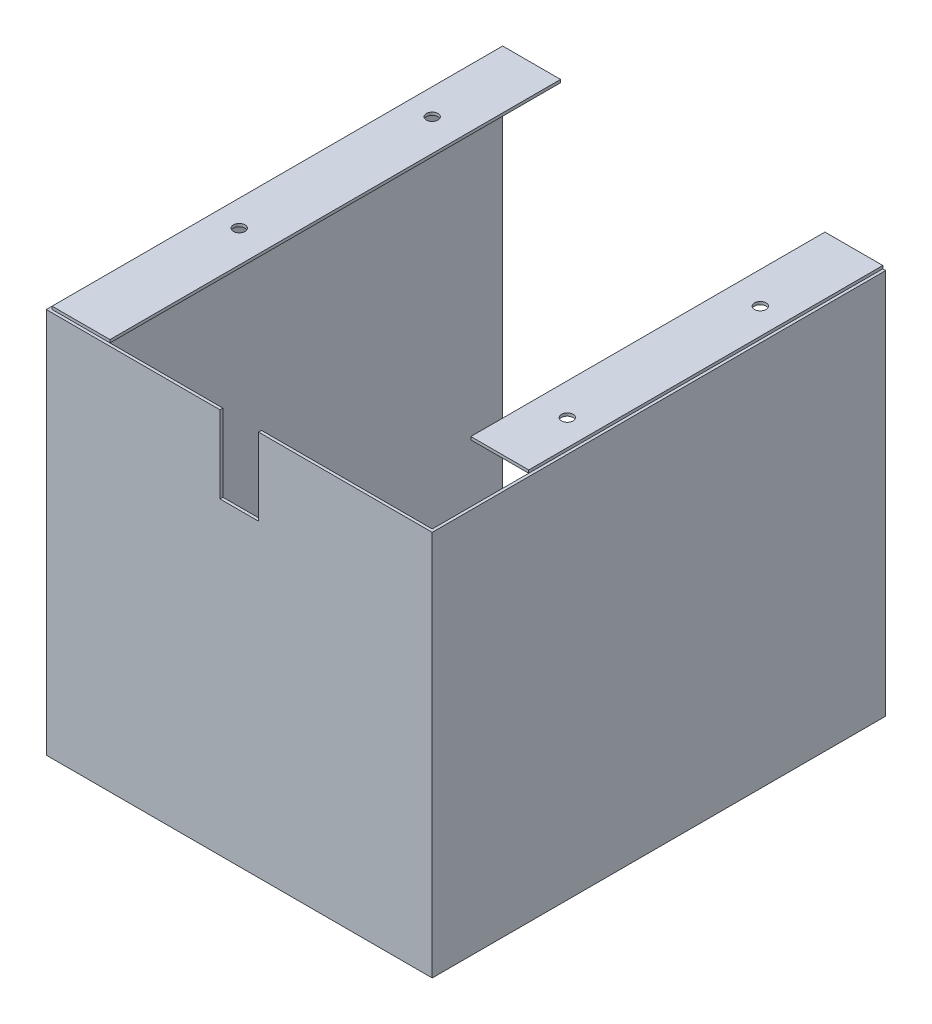
SolidWorks part; units mm, degrees
ref_plane "Front Plane" through (0, 0, 0) normal (0, 0, 1) x (1, 0, 0)
ref_plane "Top Plane" through (0, 0, 0) normal (0, 1, 0) x (1, 0, 0)
ref_plane "Right Plane" through (0, 0, 0) normal (1, 0, 0) x (0, 0, -1)
sketch "Sketch1" plane through (0, 0, 0) normal (0, 0, 1) x (1, 0, 0)
  line L1 (100, -100) -> (-100, -100)
  line L2 (100, -100) -> (100, 100)
  line L3 (100, 100) -> (-100, 100)
  line L4 (-100, -100) -> (-100, 100)
  line L5 (100, -100) -> (-100, 100) construction
  line L6 (100, 100) -> (-100, -100) construction
  point P0 (0, 0)
  dimension "D1" = 200
  dimension "D2" = 200
extrude "Boss-Extrude1" add sketch "Sketch1" along normal blind 235
shell "Shell1" thickness 1.5
sketch "Sketch2" plane through (0, 0, 235) normal (0, 0, 1) x (1, 0, 0)
  line L0 (0, 0) -> (0, 100) construction
  line L1 (100, 100) -> (-100, 100) construction
  line L3 (-10, 100) -> (10, 100)
  line L4 (-10, 100) -> (-10, 60)
  line L5 (-10, 60) -> (10, 60)
  line L6 (10, 100) -> (10, 60)
  dimension "D1" = 20
  dimension "D2" = 10
  dimension "D3" = 40
extrude "Cut-Extrude1" cut sketch "Sketch2" against normal up to next
sketch "Sketch3" plane through (0, 100, 0) normal (0, 1, 0) x (1, 0, 0)
  line L0 (-98.5, -233.5) -> (98.5, -233.5) construction
  line L1 (-98.5, 0) -> (-68.5, 0)
  line L2 (-98.5, 0) -> (-98.5, -233.5)
  line L3 (-98.5, -233.5) -> (-68.5, -233.5)
  line L4 (-68.5, 0) -> (-68.5, -233.5)
  line L5 (68.5, -183.5) -> (98.5, -183.5)
  line L6 (98.5, 0) -> (68.5, 0)
  line L7 (98.5, 0) -> (98.5, -183.5)
  line L9 (68.5, 0) -> (68.5, -183.5)
  line L10 (98.5, -233.5) -> (10, -233.5) construction
  dimension "D1" = 30
  dimension "D2" = 30
  dimension "D3" = 50
extrude "Boss-Extrude2" add sketch "Sketch3" along normal blind 1.5 separate body
sketch "Sketch5" plane through (0, 101.5, 0) normal (0, 1, 0) x (1, 0, 0)
  line L0 (0, 0) -> (0, -233.5) construction
  line L1 (10, -233.5) -> (-10, -233.5) construction
  line L2 (-100, -235) -> (-100, 0) construction
  line L4 (-68.5, 0) -> (-98.5, 0) construction
  circle A0 centre (-85, -50) radius 3
  circle A1 centre (-85, -150) radius 3
  circle A2 centre (85, -150) radius 3
  circle A3 centre (85, -50) radius 3
  point P5 (0, 0)
  dimension "D1" = 50
  dimension "D2" = 100
  dimension "D3" = 6
  dimension "D4" = 15
extrude "Cut-Extrude3" cut sketch "Sketch5" against normal blind 1.5
